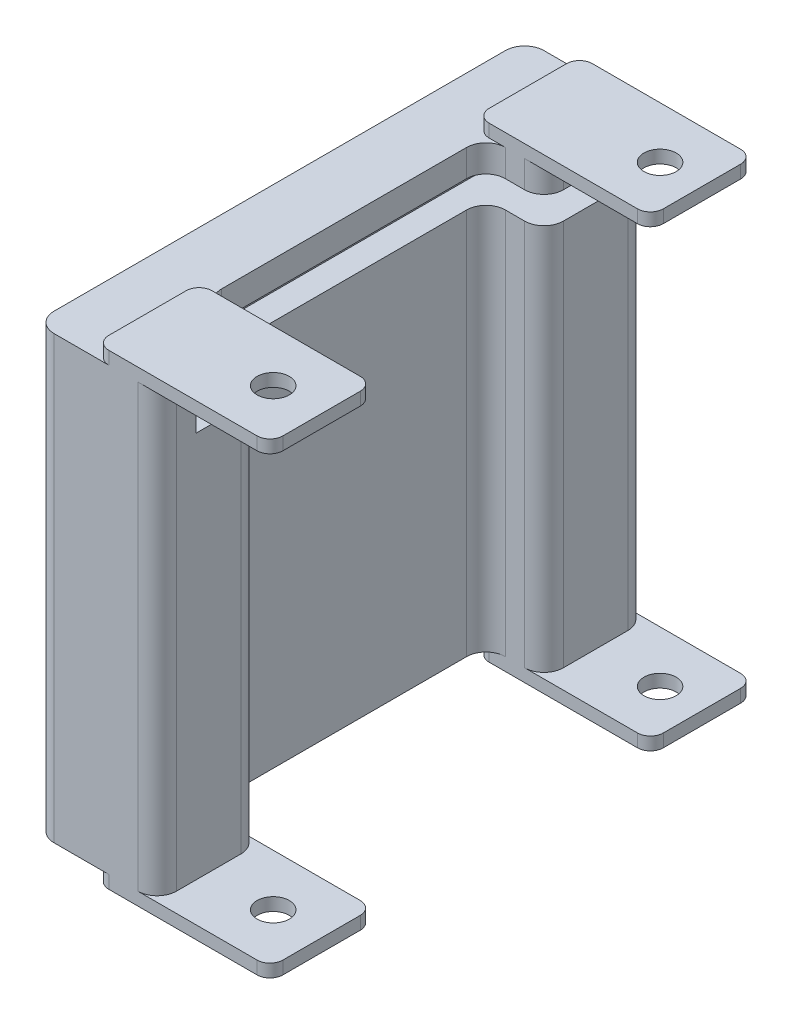
SolidWorks part; units mm, degrees
material "Aleación 1060"
ref_plane "Alzado" through (0, 0, 0) normal (0, 0, 1) x (1, 0, 0)
ref_plane "Planta" through (0, 0, 0) normal (0, 1, 0) x (1, 0, 0)
ref_plane "Vista lateral" through (0, 0, 0) normal (1, 0, 0) x (0, 0, -1)
sketch "Croquis1" plane through (0, 0, 0) normal (0, 1, 0) x (1, 0, 0)
  line L0 (0, 0) -> (9.5, 0)
  line L1 (9.5, 0) -> (9.5, 8)
  line L2 (9.5, 8) -> (5, 8)
  line L3 (5, 8) -> (5, 30)
  line L4 (5, 30) -> (9.5, 30)
  line L5 (9.5, 30) -> (9.5, 38)
  line L6 (9.5, 38) -> (0, 38)
  line L7 (0, 38) -> (0, 0)
  dimension "D1" = 38
  dimension "D2" = 8
  dimension "D3" = 8
  dimension "D4" = 5
  dimension "D5" = 9.5
  dimension "D6" = 9.5
extrude "Saliente-Extruir1" add sketch "Croquis1" along normal blind 30
fillet "Redondeo1" radius 1.5 8 edges at (0, 15, 0) (0, 15, -38) (9.5, 15, 0) (9.5, 15, -8) (9.5, 15, -30) (9.5, 15, -38) (5, 15, -8) (5, 15, -30)
sketch "Croquis2" plane through (0, 30, 0) normal (0, 1, 0) x (1, 0, 0)
  line L0 (0, 36.5) -> (0, 1.5) construction
  line L2 (0, 36.5) -> (0, 1.5)
  line L3 (1.5, 0) -> (8, 0)
  line L4 (9.5, 1.5) -> (9.5, 3)
  line L5 (9.5, 1.5) -> (9.5, 6.5) construction
  line L6 (9.5, 3) -> (3, 3)
  line L7 (3, 3) -> (3, 35)
  line L8 (3, 35) -> (9.5, 35)
  line L9 (9.5, 31.5) -> (9.5, 36.5) construction
  line L10 (9.5, 35) -> (9.5, 36.5)
  line L11 (1.5, 38) -> (8, 38)
  arc A0 (9.5, 36.5) -> (8, 38) centre (8, 36.5) ccw
  arc A2 (1.5, 38) -> (0, 36.5) centre (1.5, 36.5) ccw construction
  arc A3 (1.5, 0) -> (0, 1.5) centre (1.5, 1.5) cw
  arc A5 (1.5, 38) -> (0, 36.5) centre (1.5, 36.5) ccw
  arc A6 (8, 0) -> (9.5, 1.5) centre (8, 1.5) ccw
  dimension "D1" = 3
  dimension "D2" = 3
  dimension "D3" = 3
extrude "Saliente-Extruir2" add sketch "Croquis2" along normal blind 2.1
sketch "Croquis3" plane through (0, 32.1, 0) normal (0, 1, 0) x (1, 0, 0)
  line L0 (5, 9.5) -> (5, 28.5) construction
  line L3 (8, 8) -> (6.5, 8)
  line L4 (5, 9.5) -> (5, 28.5)
  line L5 (6.5, 30) -> (8, 30)
  line L7 (8, 38) -> (1.5, 38)
  line L8 (0, 36.5) -> (0, 1.5)
  line L9 (1.5, 0) -> (8, 0) construction
  line L10 (9.5, 31.5) -> (9.5, 36.5)
  line L11 (9.5, 6.5) -> (9.5, 1.5)
  line L12 (8, 0) -> (1.5, 0)
  arc A4 (5, 9.5) -> (6.5, 8) centre (6.5, 9.5) ccw construction
  arc A8 (1.5, 38) -> (0, 36.5) centre (1.5, 36.5) ccw
  arc A9 (0, 1.5) -> (1.5, 0) centre (1.5, 1.5) ccw
  arc A10 (0, 1.5) -> (1.5, 0) centre (1.5, 1.5) ccw construction
  arc A11 (8, 0) -> (9.5, 1.5) centre (8, 1.5) ccw
  arc A12 (8, 8) -> (9.5, 6.5) centre (8, 6.5) cw
  arc A13 (6.5, 8) -> (5, 9.5) centre (6.5, 9.5) cw
  arc A14 (8, 38) -> (9.5, 36.5) centre (8, 36.5) cw
  arc A15 (8, 30) -> (9.5, 31.5) centre (8, 31.5) ccw
  arc A16 (6.5, 30) -> (5, 28.5) centre (6.5, 28.5) ccw
extrude "Saliente-Extruir3" add sketch "Croquis3" along normal blind 2.1
sketch "Croquis4" plane through (0, 34.2, 0) normal (0, 1, 0) x (1, 0, 0)
  line L1 (4.25, 38) -> (17.75, 38)
  line L2 (4.25, 38) -> (4.25, 30)
  line L3 (4.25, 30) -> (17.75, 30)
  line L4 (17.75, 38) -> (17.75, 30)
  line L6 (4.75, 0) -> (18.25, 0)
  line L7 (4.75, 0) -> (4.75, 8)
  line L8 (4.75, 8) -> (18.25, 8)
  line L9 (18.25, 0) -> (18.25, 8)
  line L14 (9.5, 31.5) -> (9.5, 36.5) construction
  line L15 (9.5, 1.5) -> (9.5, 6.5) construction
  circle A0 centre (14.5, 4) radius 1.25
  circle A1 centre (14.5, 34) radius 1.25
  dimension "D9" = 2.5
  dimension "D10" = 2.5
  dimension "D1" = 8
  dimension "D2" = 8
  dimension "D3" = 13.5
  dimension "D4" = 13.5
  dimension "D5" = 5
  dimension "D6" = 5
  dimension "D7" = 4
  dimension "D8" = 4
extrude "Saliente-Extruir4" add sketch "Croquis4" along normal blind 1
sketch "Croquis5" plane through (0, 0, 0) normal (0, -1, 0) x (1, 0, 0)
  line L0 (4.75, 0) -> (18.25, 0)
  line L1 (4.75, 0) -> (4.75, -8)
  line L2 (4.75, -8) -> (18.25, -8)
  line L3 (18.25, 0) -> (18.25, -8)
  line L4 (4.25, -38) -> (17.75, -38)
  line L5 (4.25, -38) -> (4.25, -30)
  line L6 (4.25, -30) -> (17.75, -30)
  line L7 (17.75, -38) -> (17.75, -30)
  line L8 (1.5, 0) -> (8, 0) construction
  line L9 (9.5, -1.5) -> (9.5, -6.5) construction
  line L10 (9.5, -31.5) -> (9.5, -36.5) construction
  circle A0 centre (14.5, -34) radius 1.25
  circle A1 centre (14.5, -4) radius 1.25
  point P14 (4.75, 0)
  dimension "D7" = 2.5
  dimension "D8" = 2.5
  dimension "D1" = 8
  dimension "D2" = 8
  dimension "D3" = 13.5
  dimension "D4" = 13.5
  dimension "D5" = 4
  dimension "D6" = 4
  dimension "D9" = 5
  dimension "D10" = 5
extrude "Saliente-Extruir5" add sketch "Croquis5" along normal blind 1
fillet "Redondeo2" radius 1 16 edges at (4.75, 34.7, -8) (4.75, 34.7, 0) (4.25, 34.7, -30) (4.25, 34.7, -38) (4.25, -0.5, -38) (4.25, -0.5, -30) (4.75, -0.5, -8) (4.75, -0.5, 0) (18.25, -0.5, -8) (18.25, -0.5, 0) (17.75, -0.5, -30) (17.75, -0.5, -38) (17.75, 34.7, -30) (17.75, 34.7, -38) (18.25, 34.7, -8) (18.25, 34.7, 0)
